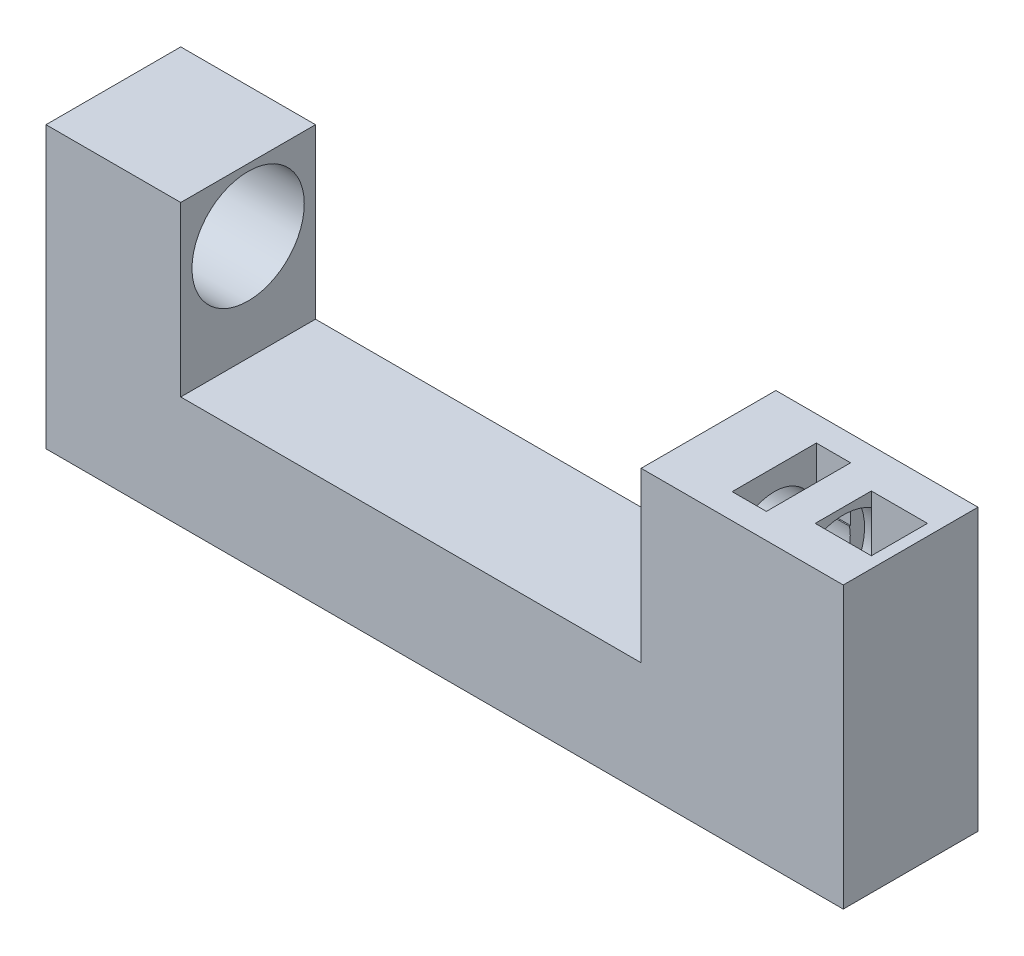
SolidWorks part; units mm, degrees
ref_plane "Front Plane" through (0, 0, 0) normal (0, 0, 1) x (1, 0, 0)
ref_plane "Top Plane" through (0, 0, 0) normal (0, 1, 0) x (1, 0, 0)
ref_plane "Right Plane" through (0, 0, 0) normal (1, 0, 0) x (0, 0, -1)
sketch "Sketch1" plane through (0, 0, 0) normal (0, 1, 0) x (1, 0, 0)
  line L1 (-32.5, 6) -> (32.5, 6)
  line L2 (-32.5, 6) -> (-32.5, -6)
  line L3 (-32.5, -6) -> (32.5, -6)
  line L4 (32.5, 6) -> (32.5, -6)
  line L5 (-32.5, 6) -> (32.5, -6) construction
  line L6 (-32.5, -6) -> (32.5, 6) construction
  point P0 (0, 0)
  dimension "D1" = 65
  dimension "D2" = 12
extrude "Boss-Extrude1" add sketch "Sketch1" along normal blind 25
sketch "Sketch2" plane through (32.5, 0, 0) normal (1, 0, 0) x (0, 0, -1)
  line L0 (0, 25) -> (0, 0) construction
  line L1 (-6, 25) -> (6, 25) construction
  circle A0 centre (0, 19.3992) radius 5
  point P7 (0, 0)
  dimension "D1" = 10
extrude "Cut-Extrude1" cut sketch "Sketch2" against normal through all
sketch "Sketch3" plane through (0, 25, 0) normal (0, 1, 0) x (1, 0, 0)
  line L0 (32.5, 6) -> (-32.5, 6) construction
  line L1 (-20.5, 6) -> (20.5, 6)
  line L2 (-20.5, 6) -> (-20.5, -6)
  line L3 (-20.5, -6) -> (20.5, -6)
  line L4 (20.5, 6) -> (20.5, -6)
  line L5 (-32.5, -6) -> (32.5, -6) construction
  line L6 (-20.5, 0) -> (-32.5, 0) construction
  line L7 (-32.5, 6) -> (-32.5, -6) construction
  line L8 (20.5, 0) -> (32.5, 0) construction
  line L9 (32.5, -6) -> (32.5, 6) construction
  dimension "D1" = 41
extrude "Cut-Extrude2" cut sketch "Sketch3" against normal blind 15
sketch "Sketch5" plane through (32.5, 0, 0) normal (1, 0, 0) x (0, 0, -1)
  circle A0 centre (0, 19.3992) radius 3.725
  circle A1 centre (0, 19.3992) radius 5
  dimension "D1" = 7.45
extrude "Boss-Extrude2" add sketch "Sketch5" against normal up to surface (8.9 mm away) from offset 3.1 up to face at (20.5, 17.5, 0) offset against normal yes
sketch "Sketch4" plane through (0, 25, 0) normal (0, 1, 0) x (1, 0, 0)
  line L0 (32.5, 0) -> (27.88, 0) construction
  line L1 (32.5, -6) -> (32.5, 6) construction
  line L3 (29.405, -3.75) -> (26.355, -3.75)
  line L4 (29.405, -3.75) -> (29.405, 3.75)
  line L5 (29.405, 3.75) -> (26.355, 3.75)
  line L6 (26.355, -3.75) -> (26.355, 3.75)
  line L7 (29.405, -3.75) -> (26.355, 3.75) construction
  line L8 (29.405, 3.75) -> (26.355, -3.75) construction
  dimension "D1" = 4.62
  dimension "D2" = 3.05
  dimension "D3" = 7.5
extrude "Cut-Extrude3" cut sketch "Sketch4" against normal blind 4.84
sketch "Sketch7" plane through (32.5, 0, 0) normal (1, 0, 0) x (0, 0, -1)
  line L1 (-6, 25) -> (6, 25)
  line L2 (-6, 25) -> (-6, 0)
  line L3 (-6, 0) -> (6, 0)
  line L4 (6, 25) -> (6, 0)
  circle A0 centre (0, 19.3992) radius 5
sketch "Sketch11" plane through (0, 25, 0) normal (0, 1, 0) x (1, 0, 0)
sketch "Sketch12" plane through (32.5, 0, 0) normal (1, 0, 0) x (0, 0, -1)
  line L0 (2.5, 24.5317) -> (6, 24.5317) construction
  line L1 (-6, 25) -> (6, 25)
  line L2 (-6, 25) -> (-6, 0)
  line L3 (-6, 0) -> (6, 0)
  line L4 (6, 25) -> (6, 0)
  line L5 (-2.5, 25) -> (2.5, 25)
  line L6 (-2.5, 25) -> (-2.5, 13.8935)
  line L7 (-2.5, 13.8935) -> (2.5, 13.8935)
  line L8 (2.5, 25) -> (2.5, 13.8935)
  line L9 (-2.5, 24.5317) -> (-6, 24.5317) construction
  point P14 (2.5, 14.049)
  point P15 (2.5, 18.7754)
  point P16 (2.5, 17.6596)
  point P17 (2.5, 13.5882)
  point P18 (2.5, 15.6916)
  point P19 (2.5, 13.8935)
  circle M9 centre (0, 19.3992) radius 5
  line M10 (-6, 0) -> (6, 0)
  line M11 (6, 0) -> (6, 25)
  line M12 (6, 25) -> (-6, 25)
  line M13 (-6, 25) -> (-6, 0)
  dimension "D1" = 5
extrude "Boss-Extrude5" add sketch "Sketch12" along normal blind 6 contours L8 L7 L6 M12 M9 M13 M10 M11 | L6 M9 | L8 M9
sketch "Sketch13" plane through (0, 25, 0) normal (0, 1, 0) x (1, 0, 0)
  line L0 (38.5, -2.5) -> (32.5, -2.5) construction
  line L1 (38.5, 2.5) -> (37.5, 2.5)
  line L2 (38.5, 2.5) -> (38.5, -2.5)
  line L3 (38.5, -2.5) -> (37.5, -2.5)
  line L4 (37.5, 2.5) -> (37.5, -2.5)
  dimension "D1" = 1
extrude "Boss-Extrude6" add sketch "Sketch13" against normal up to surface (11.1065 mm away) up to face at (35.5, 13.8935, 0)
sketch "Sketch14" plane through (0, 13.8935, 0) normal (0, 1, 0) x (1, 0, 0)
  line L1 (32.5, 2.5) -> (37.5, 2.5)
  line L2 (32.5, 2.5) -> (32.5, -2.5)
  line L3 (32.5, -2.5) -> (37.5, -2.5)
  line L4 (37.5, 2.5) -> (37.5, -2.5)
extrude "Boss-Extrude7" add sketch "Sketch14" along normal blind 4.492
